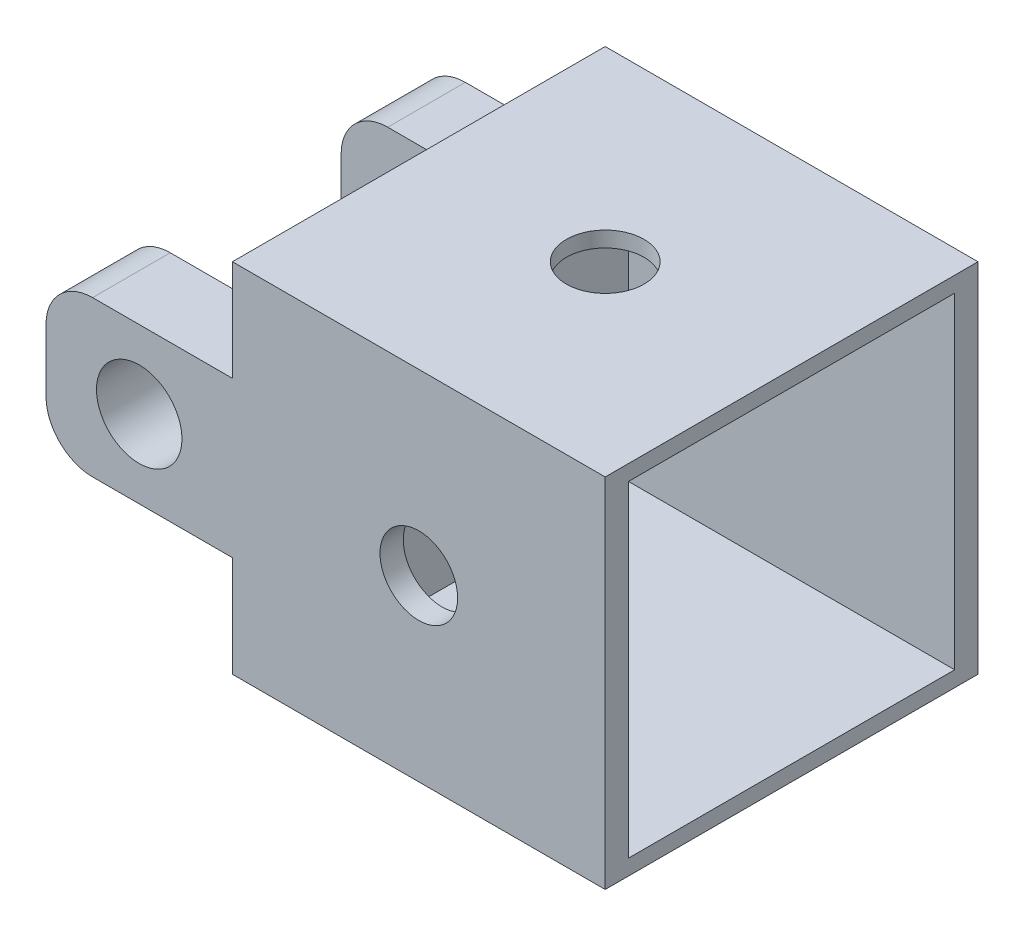
SolidWorks part; units mm, degrees
ref_plane "Front Plane" through (0, 0, 0) normal (0, 0, 1) x (1, 0, 0)
ref_plane "Top Plane" through (0, 0, 0) normal (0, 1, 0) x (1, 0, 0)
ref_plane "Right Plane" through (0, 0, 0) normal (1, 0, 0) x (0, 0, -1)
sketch "Sketch1" plane through (0, 0, 0) normal (0, 1, 0) x (1, 0, 0)
  line L1 (-12, -12) -> (12, -12)
  line L2 (-12, -12) -> (-12, 12)
  line L3 (-12, 12) -> (12, 12)
  line L4 (12, -12) -> (12, 12)
  line L5 (-12, -12) -> (12, 12) construction
  line L6 (-12, 12) -> (12, -12) construction
  point P0 (0, 0)
  dimension "D1" = 24
  dimension "D2" = 24
extrude "Boss-Extrude1" add sketch "Sketch1" along normal mid plane 23
sketch "Sketch2" plane through (12, 0, 0) normal (1, 0, 0) x (0, 0, -1)
  line L1 (-10.5, -10.5) -> (10.5, -10.5)
  line L2 (-10.5, -10.5) -> (-10.5, 10.5)
  line L3 (-10.5, 10.5) -> (10.5, 10.5)
  line L4 (10.5, -10.5) -> (10.5, 10.5)
  line L5 (-10.5, -10.5) -> (10.5, 10.5) construction
  line L6 (-10.5, 10.5) -> (10.5, -10.5) construction
  point P0 (0, 0)
  dimension "D1" = 21
  dimension "D2" = 21
extrude "Cut-Extrude1" cut sketch "Sketch2" against normal blind 21
sketch "Sketch3" plane through (0, 11.5, 0) normal (0, 1, 0) x (1, 0, 0)
  circle A0 centre (0, 0) radius 2.5
  dimension "D1" = 5
extrude "Cut-Extrude2" cut sketch "Sketch3" against normal blind 3
sketch "Sketch4" plane through (0, 0, 12) normal (0, 0, 1) x (1, 0, 0)
  circle A0 centre (0, 0) radius 2.5
  dimension "D1" = 5
extrude "Cut-Extrude3" cut sketch "Sketch4" against normal blind 3
sketch "Sketch8" plane through (-12, 0, 0) normal (-1, 0, 0) x (0, 0, 1)
  line L11 (-7, 0) -> (-7, 5)
  line L12 (13.2, 0) -> (-13.2, 0) construction
  line L13 (-7, 5) -> (-12, 5)
  line L14 (-12, 11.5) -> (-12, -11.5) construction
  line L15 (-12, 5) -> (-12, 0)
  line L16 (-12, 0) -> (-12, -5)
  line L17 (-12, -5) -> (-7, -5)
  line L18 (-7, -5) -> (-7, 0)
  dimension "D1" = 5
  dimension "D2" = 5
extrude "Boss-Extrude3" add sketch "Sketch8" along normal blind 12
sketch "Sketch9" plane through (0, 0, -12) normal (0, 0, -1) x (-1, 0, 0)
  line L0 (13.2, 0) -> (-13.2, 0) construction
  line L1 (24, 5) -> (24, -5) construction
  circle A0 centre (18, 0) radius 2.75
  dimension "D1" = 5.5
  dimension "D2" = 6
extrude "Cut-Extrude5" cut sketch "Sketch9" against normal blind 5
fillet "Fillet2" radius 3 2 edges at (-24, -5, -9.5) (-24, 5, -9.5)
mirror "Mirror1" about plane through (0, 0, 0) normal (0, 0, 1) of "Boss-Extrude3", "Cut-Extrude5", "Fillet2"
